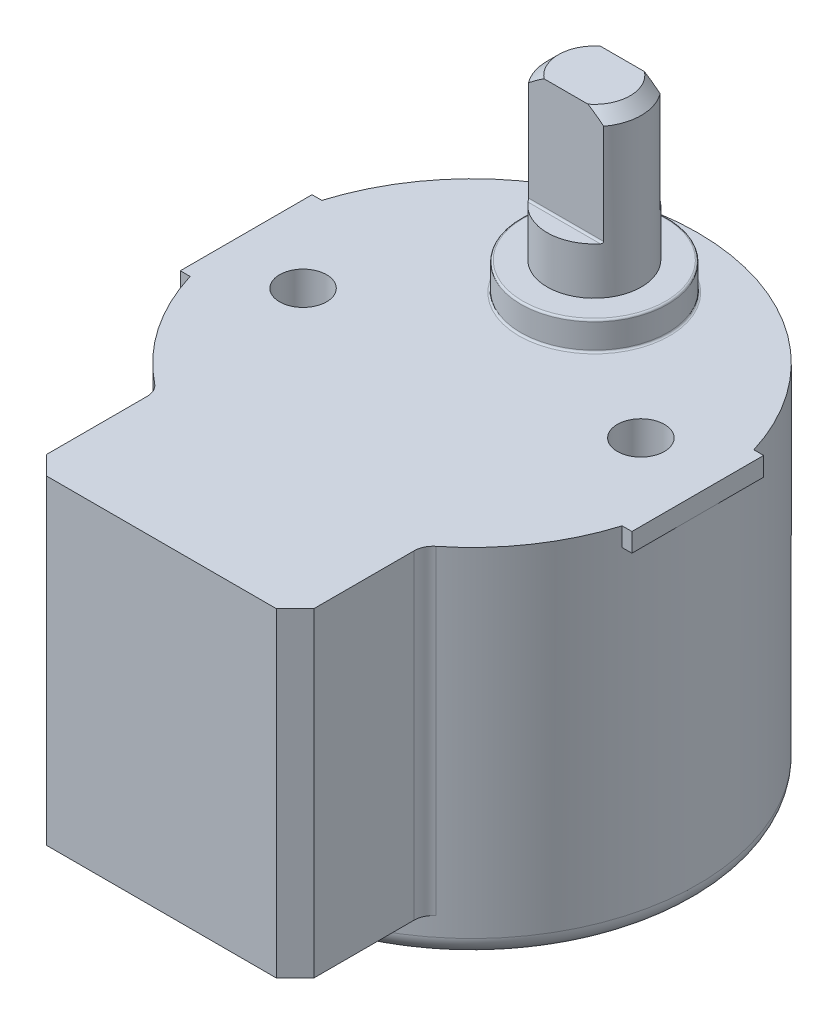
SolidWorks part; units mm, degrees
ref_plane "Front Plane" through (0, 0, 0) normal (0, 0, 1) x (1, 0, 0)
ref_plane "Top Plane" through (0, 0, 0) normal (0, 1, 0) x (1, 0, 0)
ref_plane "Right Plane" through (0, 0, 0) normal (1, 0, 0) x (0, 0, -1)
sketch "Sketch1" plane through (0, 0, 0) normal (0, 1, 0) x (1, 0, 0)
  line L0 (-7.1, -8.9053) -> (-7.1, -16.5)
  line L1 (-7.1, -16.5) -> (7.1, -16.5)
  line L2 (7.1, -16.5) -> (7.1, -8.9053)
  line L3 (0, 0) -> (0, -16.5) construction
  line L4 (7.1, -8.9053) -> (-7.1, -8.9053)
  circle A0 centre (0, 0) radius 12
  dimension "D1" = 24
  dimension "D2" = 14.2
  dimension "D3" = 16.5
extrude "Boss-Extrude1" add sketch "Sketch1" along normal blind 19 contours A0
ref_plane "Plane1" through (0, 2, 0) normal (0, -1, 0) x (-1, 0, 0)
sketch "Sketch2" plane through (0, 2, 0) normal (0, -1, 0) x (-1, 0, 0)
  line L0 (7.1, -8.9053) -> (7.1, -16.5) construction
  line L1 (-7.1, -8.9053) -> (7.1, -8.9053) construction
  line L2 (-7.1, -16.5) -> (-7.1, -8.9053) construction
  line L3 (7.1, -16.5) -> (-7.1, -16.5) construction
  line L4 (7.1, -8.9053) -> (7.1, -16.5)
  line L5 (-7.1, -8.9053) -> (7.1, -8.9053)
  line L6 (-7.1, -16.5) -> (-7.1, -8.9053)
  line L7 (7.1, -16.5) -> (-7.1, -16.5)
extrude "Boss-Extrude2" add sketch "Sketch2" against normal up to surface (17 mm away) up to face at (0, 19, 12)
sketch "Sketch3" plane through (0, 19, 0) normal (0, 1, 0) x (1, 0, 0)
  line L0 (-15.5, 0) -> (13.892, 0) construction
  line L1 (0, 0) -> (0, -2.2302) construction
  line L2 (-15.5, -3.5) -> (-8, -3.5)
  line L3 (-8, -3.5) -> (-8, 3.5)
  line L4 (-8, 3.5) -> (-15.5, 3.5)
  line L5 (8, -3.5) -> (8, 3.5)
  line L6 (15.5, -3.5) -> (8, -3.5)
  line L7 (8, 3.5) -> (15.5, 3.5)
  circle A0 centre (-15.5, 0) radius 2.05
  arc A1 (-15.5, 3.5) -> (-15.5, -3.5) centre (-15.5, 0) ccw
  circle A2 centre (15.5, 0) radius 2.05
  arc A3 (15.5, 3.5) -> (15.5, -3.5) centre (15.5, 0) cw
  dimension "D1" = 4.1
  dimension "D2" = 7
  dimension "D3" = 15.5
  dimension "D4" = 8
extrude "Boss-Extrude3" add sketch "Sketch3" against normal blind 1
sketch "Sketch4" plane through (0, 0, 0) normal (1, 0, 0) x (0, 0, -1)
  line L0 (6.5, 23.5317) -> (6.5, 16.8972) construction
  line L1 (0, -3.0186) -> (0, 25.3557) construction
  line L2 (6.5, 19) -> (2.6, 19)
  line L3 (12, 19) -> (3.5, 19) construction
  line L4 (2.6, 19) -> (2.6, 20.5)
  line L5 (2.6, 20.5) -> (4, 20.5)
  line L6 (4, 20.5) -> (4, 29)
  line L7 (4, 29) -> (6.5, 29)
  line L8 (6.5, 29) -> (6.5, 19)
  point P13 (3.3, 20.5)
  dimension "D1" = 6.5
  dimension "D2" = 7.8
  dimension "D3" = 5
  dimension "D4" = 1.5
  dimension "D5" = 10
revolve "Revolve1" add sketch "Sketch4" angle 360 about L0
chamfer "Chamfer1" distance 0.6 angle 45 1 edges at (0, 29, -4)
sketch "Sketch5" plane through (0, 29, 0) normal (0, 1, 0) x (1, 0, 0)
  line L0 (0, 6.5) -> (4.6829, 6.5) construction
  line L1 (0, 6.5) -> (0, 11.3585) construction
  line L2 (-3, 10) -> (3, 10)
  line L3 (-3, 10) -> (-3, 8)
  line L4 (-3, 8) -> (3, 8)
  line L5 (3, 10) -> (3, 8)
  line L6 (-3, 5) -> (3, 5)
  line L7 (3, 3) -> (3, 5)
  line L8 (-3, 3) -> (3, 3)
  line L9 (-3, 3) -> (-3, 5)
  dimension "D1" = 1.5
  dimension "D2" = 2
  dimension "D3" = 6
extrude "Cut-Extrude1" cut sketch "Sketch5" against normal blind 6
fillet "Fillet1" radius 0.1 2 edges at (0, 23, -8) (0, 23, -5)
chamfer "Chamfer2" distance 1 angle 45 2 edges at (-7.1, 10.5, 16.5) (7.1, 10.5, 16.5)
fillet "Fillet2" radius 1 2 edges at (-7.1, 10.5, 9.6742) (7.1, 10.5, 9.6742)
fillet "Fillet3" radius 0.1 2 edges at (0, 20.5, -2.6) (0, 19, -2.6)
fillet "Fillet4" radius 1 1 edges at (0, 0, 12)
sketch "Sketch6" plane through (0, 19, 0) normal (0, 1, 0) x (1, 0, 0)
  line L0 (0, 0) -> (0, -6.2723) construction
  line L1 (-21.2565, 4.7434) -> (-12, 4.7434)
  line L2 (-21.2565, 4.7434) -> (-21.2565, -5.4103)
  line L3 (-21.2565, -5.4103) -> (-12, -5.4103)
  line L4 (-12, 4.7434) -> (-12, -5.4103)
  line L5 (21.2565, -5.4103) -> (12, -5.4103)
  line L6 (12, 4.7434) -> (12, -5.4103)
  line L7 (21.2565, 4.7434) -> (12, 4.7434)
  line L8 (21.2565, 4.7434) -> (21.2565, -5.4103)
  dimension "D1" = 12
extrude "Cut-Extrude2" cut sketch "Sketch6" against normal through all
sketch "Sketch7" plane through (0, 19, 0) normal (0, 1, 0) x (1, 0, 0)
  circle A0 centre (7.9316, 1.0442) radius 1.45 construction
  circle A1 centre (-7.9316, -1.0442) radius 1.45 construction
  circle A2 centre (7.9316, 1.0442) radius 1.45
  circle A3 centre (-7.9316, -1.0442) radius 1.45
sketch "Sketch8" plane through (0, 19, 0) normal (0, 1, 0) x (1, 0, 0)
  circle A0 centre (-7.9316, -1.0442) radius 1.25
  circle A1 centre (7.9316, 1.0442) radius 1.25
  dimension "D1" = 2.5
extrude "Cut-Extrude3" cut sketch "Sketch8" against normal blind 3
